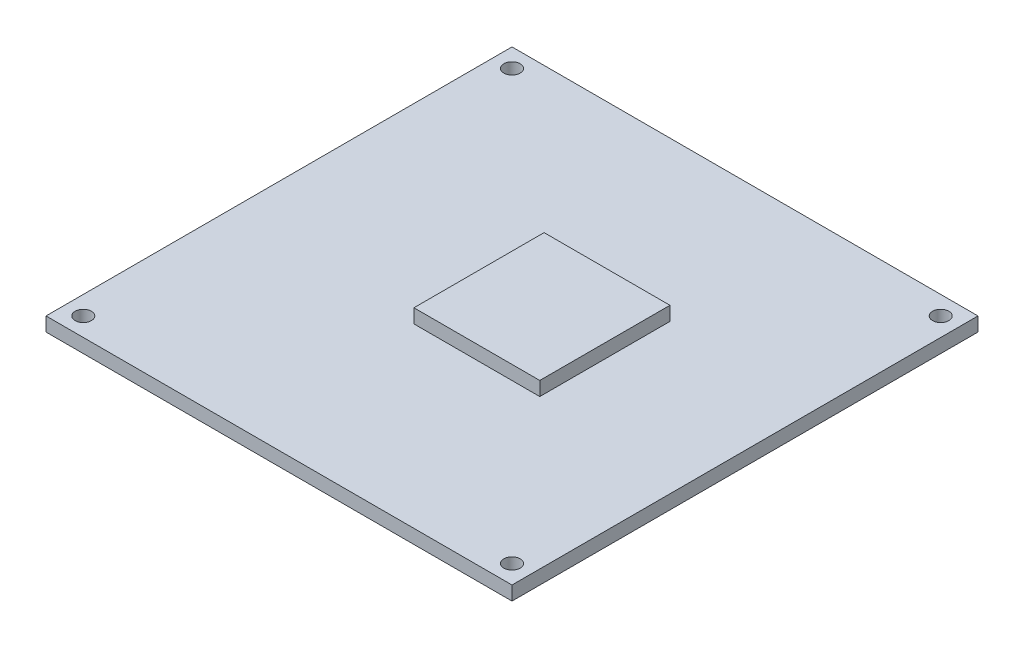
SolidWorks part; units mm, degrees
ref_plane "前视基准面" through (0, 0, 0) normal (0, 0, 1) x (1, 0, 0)
ref_plane "上视基准面" through (0, 0, 0) normal (0, 1, 0) x (1, 0, 0)
ref_plane "右视基准面" through (0, 0, 0) normal (1, 0, 0) x (0, 0, -1)
sketch "草图1" plane through (0, 0, 0) normal (0, 1, 0) x (1, 0, 0)
  line L0 (0, 0) -> (0, 50) construction
  line L1 (-50, 50) -> (50, 50)
  line L2 (-50, 50) -> (-50, -50)
  line L3 (-50, -50) -> (50, -50)
  line L4 (50, 50) -> (50, -50)
  line L5 (-50, 50) -> (50, -50) construction
  line L6 (-50, -50) -> (50, 50) construction
  line L7 (0, 0) -> (50, 0) construction
  circle A0 centre (46, 46) radius 1.75
  circle A1 centre (46, -46) radius 1.75
  circle A2 centre (-46, -46) radius 1.75
  circle A3 centre (-46, 46) radius 1.75
  point P0 (0, 0)
  dimension "D3" = 3.5
  dimension "D1" = 100
  dimension "D2" = 100
  dimension "D4" = 4
extrude "凸台-拉伸1" add sketch "草图1" along normal blind 3
sketch "草图2" plane through (0, 3, 0) normal (0, 1, 0) x (1, 0, 0)
  line L1 (-9.0398, -12.005) -> (17.9673, -12.005)
  line L2 (-9.0398, -12.005) -> (-9.0398, 15.9265)
  line L3 (-9.0398, 15.9265) -> (17.9673, 15.9265)
  line L4 (17.9673, -12.005) -> (17.9673, 15.9265)
extrude "凸台-拉伸2" add sketch "草图2" along normal blind 3
